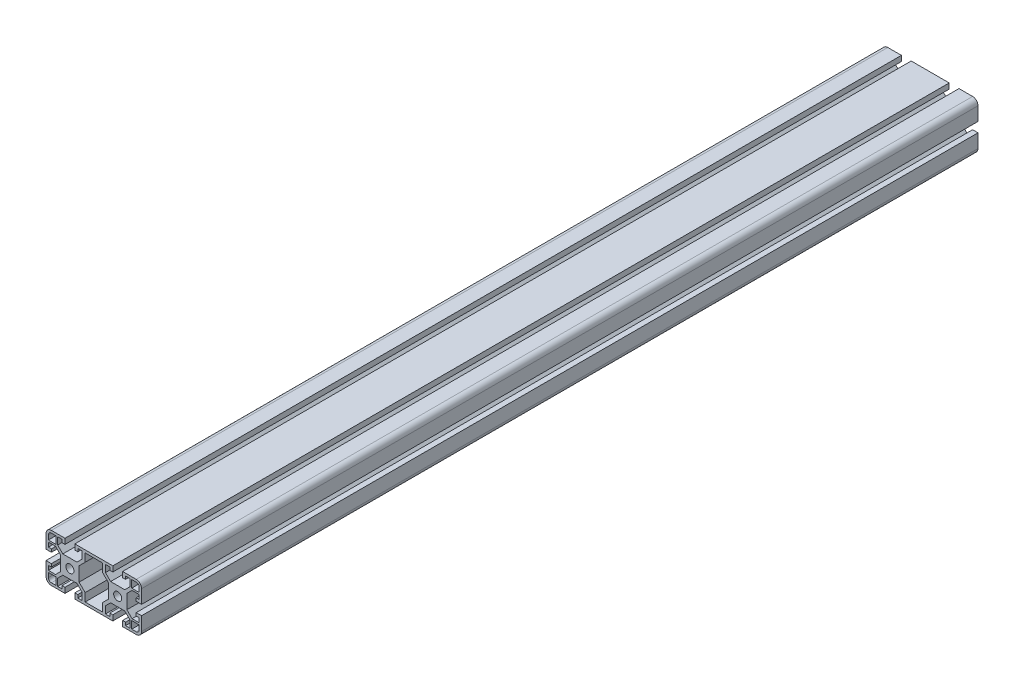
SolidWorks part; units mm, degrees
ref_plane "Front Plane" through (0, 0, 0) normal (0, 0, 1) x (1, 0, 0)
ref_plane "Top Plane" through (0, 0, 0) normal (0, 1, 0) x (1, 0, 0)
ref_plane "Right Plane" through (0, 0, 0) normal (1, 0, 0) x (0, 0, -1)
sketch "Sketch1" plane through (0, 0, 0) normal (0, 0, 1) x (1, 0, 0)
  line L0 (0, 17.8) -> (0, -17.8) construction
  line B0 (38, -15.5) -> (38, -11.75)
  line B1 (38, -11.75) -> (31.75, -11.75)
  line B2 (31.75, -11.75) -> (31.75, -18)
  line B3 (31.75, -18) -> (35.5, -18)
  arc B4 (35.5, -18) -> (38, -15.5) centre (35.5, -15.5) ccw
  line B5 (-38, 15.5) -> (-38, 11.75)
  line B6 (-38, 11.75) -> (-31.75, 11.75)
  line B7 (-31.75, 11.75) -> (-31.75, 18)
  line B8 (-31.75, 18) -> (-35.5, 18)
  arc B9 (-35.5, 18) -> (-38, 15.5) centre (-35.5, 15.5) ccw
  line B10 (24.1, -20) -> (35.5, -20)
  arc B11 (35.5, -20) -> (40, -15.5) centre (35.5, -15.5) ccw
  line B12 (40, -15.5) -> (40, -4.1)
  line B13 (40, -4.1) -> (35.5, -4.1)
  line B14 (35.5, -4.1) -> (35.5, -6.6)
  line B15 (35.5, -6.6) -> (38, -6.6)
  line B16 (38, -6.6) -> (38, -10.25)
  line B17 (38, -10.25) -> (32.0178, -10.25)
  line B18 (32.0178, -10.25) -> (27.7, -5.9322)
  line B19 (27.7, -5.9322) -> (27.7, 5.9322)
  line B20 (27.7, 5.9322) -> (32.0178, 10.25)
  line B21 (32.0178, 10.25) -> (38, 10.25)
  line B22 (38, 10.25) -> (38, 6.6)
  line B23 (38, 6.6) -> (35.5, 6.6)
  line B24 (35.5, 6.6) -> (35.5, 4.1)
  line B25 (35.5, 4.1) -> (40, 4.1)
  line B26 (40, 4.1) -> (40, 15.5)
  arc B27 (40, 15.5) -> (35.5, 20) centre (35.5, 15.5) ccw
  line B28 (35.5, 20) -> (24.1, 20)
  line B29 (24.1, 20) -> (24.1, 15.5)
  line B30 (24.1, 15.5) -> (26.6, 15.5)
  line B31 (26.6, 15.5) -> (26.6, 18)
  line B32 (26.6, 18) -> (30.25, 18)
  line B33 (30.25, 18) -> (30.25, 12.0178)
  line B34 (30.25, 12.0178) -> (25.9322, 7.7)
  line B35 (25.9322, 7.7) -> (14.0678, 7.7)
  line B36 (14.0678, 7.7) -> (9.75, 12.0178)
  line B37 (9.75, 12.0178) -> (9.75, 18)
  line B38 (9.75, 18) -> (13.4, 18)
  line B39 (13.4, 18) -> (13.4, 15.5)
  line B40 (13.4, 15.5) -> (15.9, 15.5)
  line B41 (15.9, 15.5) -> (15.9, 20)
  line B42 (15.9, 20) -> (-15.9, 20)
  line B43 (-15.9, 20) -> (-15.9, 15.5)
  line B44 (-15.9, 15.5) -> (-13.4, 15.5)
  line B45 (-13.4, 15.5) -> (-13.4, 18)
  line B46 (-13.4, 18) -> (-9.75, 18)
  line B47 (-9.75, 18) -> (-9.75, 12.0178)
  line B48 (-9.75, 12.0178) -> (-14.0678, 7.7)
  line B49 (-14.0678, 7.7) -> (-25.9322, 7.7)
  line B50 (-25.9322, 7.7) -> (-30.25, 12.0178)
  line B51 (-30.25, 12.0178) -> (-30.25, 18)
  line B52 (-30.25, 18) -> (-26.6, 18)
  line B53 (-26.6, 18) -> (-26.6, 15.5)
  line B54 (-26.6, 15.5) -> (-24.1, 15.5)
  line B55 (-24.1, 15.5) -> (-24.1, 20)
  line B56 (-24.1, 20) -> (-35.5, 20)
  arc B57 (-35.5, 20) -> (-40, 15.5) centre (-35.5, 15.5) ccw
  line B58 (-40, 15.5) -> (-40, 4.1)
  line B59 (-40, 4.1) -> (-35.5, 4.1)
  line B60 (-35.5, 4.1) -> (-35.5, 6.6)
  line B61 (-35.5, 6.6) -> (-38, 6.6)
  line B62 (-38, 6.6) -> (-38, 10.25)
  line B63 (-38, 10.25) -> (-32.0178, 10.25)
  line B64 (-32.0178, 10.25) -> (-27.7, 5.9322)
  line B65 (-27.7, 5.9322) -> (-27.7, -5.9322)
  line B66 (-27.7, -5.9322) -> (-32.0178, -10.25)
  line B67 (-32.0178, -10.25) -> (-38, -10.25)
  line B68 (-38, -10.25) -> (-38, -6.6)
  line B69 (-38, -6.6) -> (-35.5, -6.6)
  line B70 (-35.5, -6.6) -> (-35.5, -4.1)
  line B71 (-35.5, -4.1) -> (-40, -4.1)
  line B72 (-40, -4.1) -> (-40, -15.5)
  arc B73 (-40, -15.5) -> (-35.5, -20) centre (-35.5, -15.5) ccw
  line B74 (-35.5, -20) -> (-24.1, -20)
  line B75 (-24.1, -20) -> (-24.1, -15.5)
  line B76 (-24.1, -15.5) -> (-26.6, -15.5)
  line B77 (-26.6, -15.5) -> (-26.6, -18)
  line B78 (-26.6, -18) -> (-30.25, -18)
  line B79 (-30.25, -18) -> (-30.25, -12.0178)
  line B80 (-30.25, -12.0178) -> (-25.9322, -7.7)
  line B81 (-25.9322, -7.7) -> (-14.0678, -7.7)
  line B82 (-14.0678, -7.7) -> (-9.75, -12.0178)
  line B83 (-9.75, -12.0178) -> (-9.75, -18)
  line B84 (-9.75, -18) -> (-13.4, -18)
  line B85 (-13.4, -18) -> (-13.4, -15.5)
  line B86 (-13.4, -15.5) -> (-15.9, -15.5)
  line B87 (-15.9, -15.5) -> (-15.9, -20)
  line B88 (-15.9, -20) -> (15.9, -20)
  line B89 (15.9, -20) -> (15.9, -15.5)
  line B90 (15.9, -15.5) -> (13.4, -15.5)
  line B91 (13.4, -15.5) -> (13.4, -18)
  line B92 (13.4, -18) -> (9.75, -18)
  line B93 (9.75, -18) -> (9.75, -12.0178)
  line B94 (9.75, -12.0178) -> (14.0678, -7.7)
  line B95 (14.0678, -7.7) -> (25.9322, -7.7)
  line B96 (25.9322, -7.7) -> (30.25, -12.0178)
  line B97 (30.25, -12.0178) -> (30.25, -18)
  line B98 (30.25, -18) -> (26.6, -18)
  line B99 (26.6, -18) -> (26.6, -15.5)
  line B100 (26.6, -15.5) -> (24.1, -15.5)
  line B101 (24.1, -15.5) -> (24.1, -20)
  line B102 (-7.25, -10.9822) -> (-7.25, -17.8)
  line B103 (-7.25, -17.8) -> (7.25, -17.8)
  line B104 (7.25, -17.8) -> (7.25, -10.9822)
  line B105 (7.25, -10.9822) -> (12.3, -5.9322)
  line B106 (12.3, -5.9322) -> (12.3, 5.9322)
  line B107 (12.3, 5.9322) -> (7.25, 10.9822)
  line B108 (7.25, 10.9822) -> (7.25, 17.8)
  line B109 (7.25, 17.8) -> (-7.25, 17.8)
  line B110 (-7.25, 17.8) -> (-7.25, 10.9822)
  line B111 (-7.25, 10.9822) -> (-12.3, 5.9322)
  line B112 (-12.3, 5.9322) -> (-12.3, -5.9322)
  line B113 (-12.3, -5.9322) -> (-7.25, -10.9822)
  circle B114 centre (-20, 0) radius 3.4
  circle B115 centre (20, 0) radius 3.4
  line B116 (-35.5, -18) -> (-31.75, -18)
  line B117 (-31.75, -18) -> (-31.75, -11.75)
  line B118 (-31.75, -11.75) -> (-38, -11.75)
  line B119 (-38, -11.75) -> (-38, -15.5)
  arc B120 (-38, -15.5) -> (-35.5, -18) centre (-35.5, -15.5) ccw
  line B121 (35.5, 18) -> (31.75, 18)
  line B122 (31.75, 18) -> (31.75, 11.75)
  line B123 (31.75, 11.75) -> (38, 11.75)
  line B124 (38, 11.75) -> (38, 15.5)
  arc B125 (38, 15.5) -> (35.5, 18) centre (35.5, 15.5) ccw
sketch_block_instance "S8-4080-1"
sketch_block "S8-4080"
extrude "Boss-Extrude1" add sketch "Sketch1" along normal blind 700
